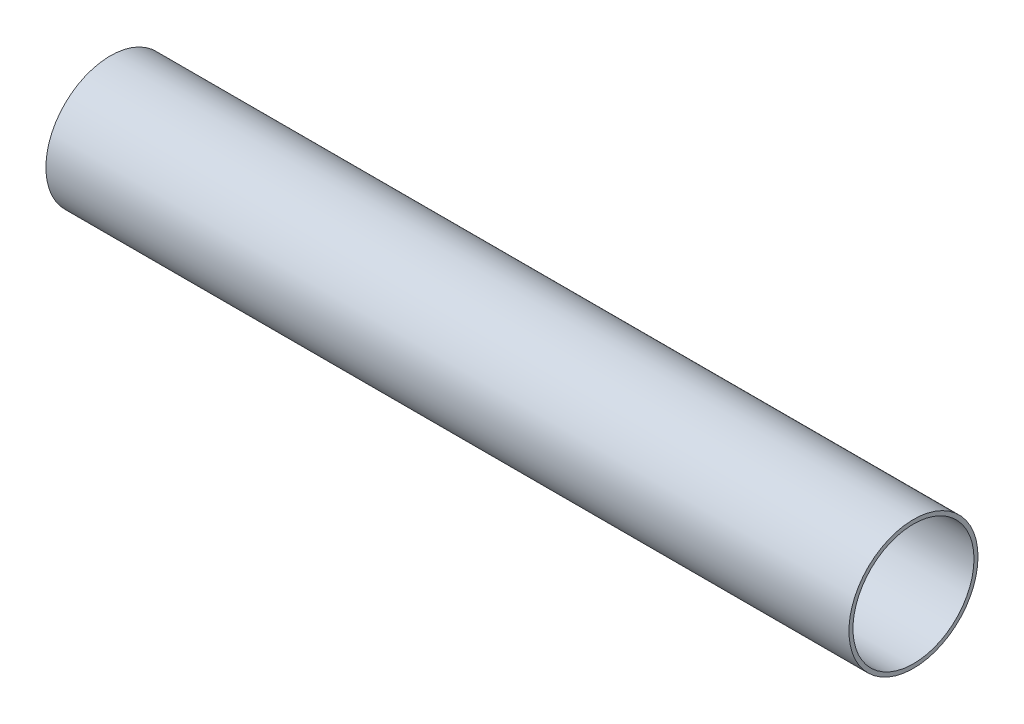
SolidWorks part; units mm, degrees
ref_plane "Front Plane" through (0, 0, 0) normal (0, 0, 1) x (1, 0, 0)
ref_plane "Top Plane" through (0, 0, 0) normal (0, 1, 0) x (1, 0, 0)
ref_plane "Right Plane" through (0, 0, 0) normal (1, 0, 0) x (0, 0, -1)
sketch "Sketch1" plane through (0, 0, 0) normal (1, 0, 0) x (0, 0, -1)
  circle A0 centre (0, 0) radius 14.2875
  circle A1 centre (0, 0) radius 13.3985
extrude "Boss-Extrude1" add sketch "Sketch1" along normal mid plane 177.8
